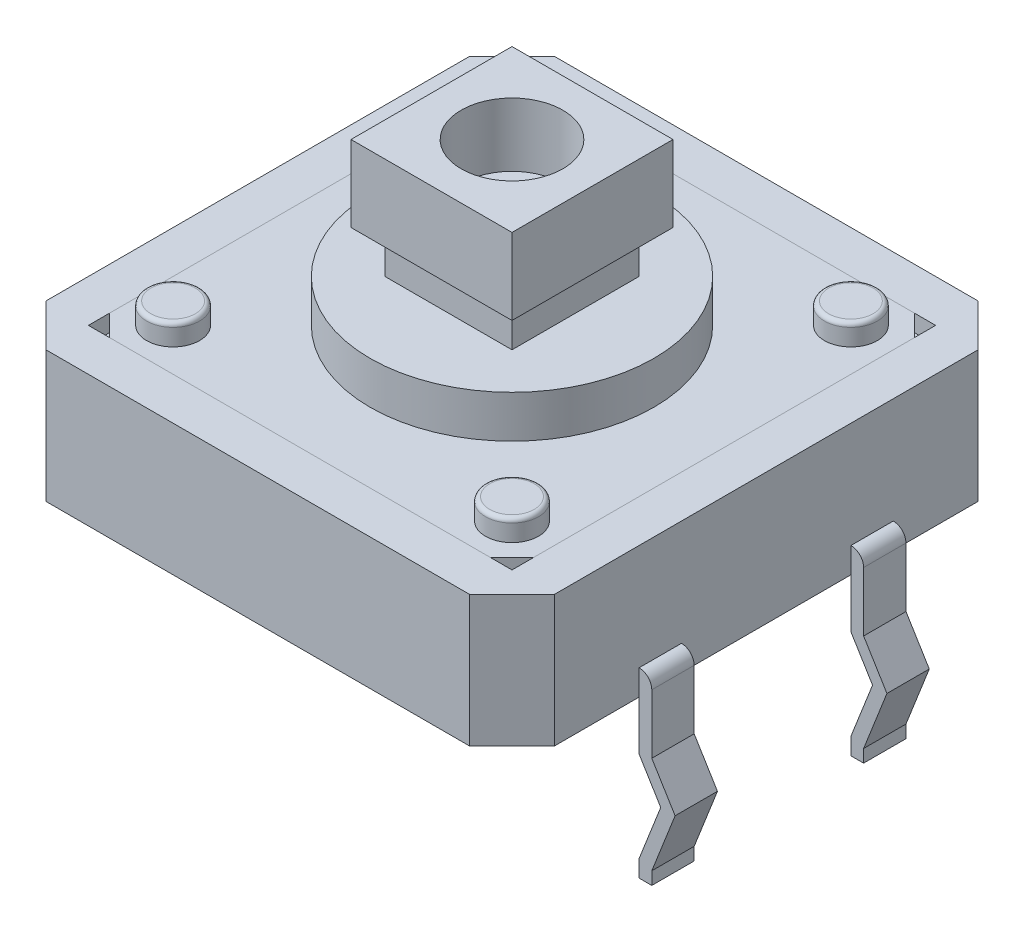
SolidWorks part; units mm, degrees
other "Markup1"
sketch "Sketch10" plane through (-6.85, 6.9, 6) normal (-0.3058, 0.046, 0.951) x (0.9335, 0.2107, 0.29)
sketch "Sketch13" plane through (-6.85, 6.9, 6) normal (-0.3058, 0.046, 0.951) x (0.9335, 0.2107, 0.29)
ref_plane "Front Plane" through (0, 0, 0) normal (0, 0, 1) x (1, 0, 0)
ref_plane "Top Plane" through (0, 0, 0) normal (0, 1, 0) x (1, 0, 0)
ref_plane "Right Plane" through (0, 0, 0) normal (1, 0, 0) x (0, 0, -1)
sketch "Sketch1" plane through (0, 0, 0) normal (0, 1, 0) x (1, 0, 0)
  line L0 (-5, 6) -> (-6, 5)
  line L1 (5, -6) -> (-5, -6)
  line L2 (6, -5) -> (6, 5)
  line L3 (5, 6) -> (-5, 6)
  line L4 (-6, -5) -> (-6, 5)
  line L5 (6, -6) -> (-6, 6) construction
  line L6 (6, 6) -> (-6, -6) construction
  line L7 (-5, -6) -> (-6, -5)
  line L8 (6, -5) -> (5, -6)
  line L9 (6, 5) -> (5, 6)
  point P0 (0, 0)
  dimension "D1" = 12
extrude "Boss-Extrude1" add sketch "Sketch1" along normal blind 3.1
sketch "Sketch2" plane through (0, 3.1, 0) normal (0, 1, 0) x (1, 0, 0)
  line L1 (5, -5) -> (-5, -5)
  line L2 (5, -5) -> (5, 5)
  line L3 (5, 5) -> (-5, 5)
  line L4 (-5, -5) -> (-5, 5)
  line L5 (5, -5) -> (-5, 5) construction
  line L6 (5, 5) -> (-5, -5) construction
  point P0 (0, 0)
  dimension "D1" = 10
extrude "Cut-Extrude1" cut sketch "Sketch2" against normal blind 0.4
sketch "Sketch3" plane through (0, 2.7, 0) normal (0, 1, 0) x (1, 0, 0)
  line L1 (4, -4) -> (-4, -4) construction
  line L2 (4, -4) -> (4, 4) construction
  line L3 (4, 4) -> (-4, 4) construction
  line L4 (-4, -4) -> (-4, 4) construction
  line L5 (4, -4) -> (-4, 4) construction
  line L6 (4, 4) -> (-4, -4) construction
  circle A0 centre (-4, 4) radius 0.625
  circle A1 centre (4, 4) radius 0.625
  circle A2 centre (-4, -4) radius 0.625
  circle A3 centre (4, -4) radius 0.625
  point P0 (0, 0)
  dimension "D2" = 1.25
  dimension "D1" = 8
extrude "Boss-Extrude2" add sketch "Sketch3" along normal blind 0.9
fillet "Fillet1" radius 0.1 4 edges at (4, 3.6, -3.375) (4, 3.6, 4.625) (-4, 3.6, 4.625) (-4, 3.6, -3.375)
sketch "Sketch4" plane through (0, 2.7, 0) normal (0, 1, 0) x (1, 0, 0)
  line L0 (5, 5) -> (-5, 5) construction
  line L1 (4.5, -5) -> (-4.5, -5)
  line L2 (5, -4.5) -> (5, 4.5)
  line L3 (4.5, 5) -> (-4.5, 5)
  line L4 (-5, -4.5) -> (-5, 4.5)
  line L5 (5, -5) -> (-5, 5) construction
  line L6 (5, 5) -> (-5, -5) construction
  line L9 (-5, 5) -> (-5, -5) construction
  line L10 (-4.5, 5) -> (-5, 4.5)
  line L11 (5, 4.5) -> (4.5, 5)
  line L12 (-4.5, -5) -> (-5, -4.5)
  line L13 (5, -4.5) -> (4.5, -5)
  circle A0 centre (0, 0) radius 3.35
  point P0 (0, 0)
  dimension "D2" = 6.7
extrude "Boss-Extrude3" add sketch "Sketch4" along normal blind 0.4 separate body
sketch "Sketch5" plane through (0, 0, 0) normal (0, 0, 1) x (1, 0, 0)
  line L1 (6, 3.1) -> (6, 0) construction
  line L2 (6, 0.6) -> (6, -1.1643)
  line L3 (6, -3.7) -> (6.3, -3.7)
  line L4 (6.3, -3.7) -> (6.3, -3.4)
  line L5 (6.3, -3.4) -> (6.85, -2)
  line L6 (6.85, -2) -> (6.3, -1.1)
  line L7 (6.3, -1.1) -> (6.3, 0.3)
  line L10 (6, -3.3) -> (6, -3.7)
  line L11 (6, 0.6) -> (6.3033, 0.6) construction
  line L12 (6.5107, -2) -> (6, -1.1643)
  line L13 (6, 0.3) -> (6.3, 0.3) construction
  line L14 (6.5107, -2) -> (6, -3.3)
  arc A0 (6, 0.6) -> (6.3, 0.3) centre (6, 0.3) cw
  point P15 (6.15, -3.7)
  dimension "D1" = 2.5
  dimension "D2" = 6.85
  dimension "D3" = 0.3
  dimension "D4" = 6.15
  dimension "D5" = 2
  dimension "D6" = 3.7
  dimension "D7" = 0.9
  dimension "D8" = 1.4
  dimension "D9" = 0.1
extrude "Boss-Extrude4" add sketch "Sketch5" along normal blind 3 and the other way blind 3 separate body
sketch "Sketch6" plane through (0, 0, 0) normal (0, 1, 0) x (1, 0, 0)
  line L5 (6, 2) -> (6.85, 2)
  line L6 (6, 2) -> (6, -2)
  line L7 (6, -2) -> (6.85, -2)
  line L8 (6.85, 2) -> (6.85, -2)
  line L9 (6, -5) -> (6, 5) construction
  line L11 (6.85, 3) -> (6.85, -3) construction
  point P8 (6, 0)
  dimension "D1" = 4
extrude "Cut-Extrude2" cut sketch "Sketch6" against normal through all both and the other way through all
sketch "Sketch7" plane through (0, 2.7, 0) normal (0, 1, 0) x (1, 0, 0)
  circle A0 centre (0, 0) radius 3.35 construction
  circle A1 centre (0, 0) radius 3.35
extrude "Boss-Extrude5" add sketch "Sketch7" along normal blind 1.4 separate body
sketch "Sketch8" plane through (0, 4.1, 0) normal (0, 1, 0) x (1, 0, 0)
  line L1 (1.5, -1.5) -> (-1.5, -1.5)
  line L2 (1.5, -1.5) -> (1.5, 1.5)
  line L3 (1.5, 1.5) -> (-1.5, 1.5)
  line L4 (-1.5, -1.5) -> (-1.5, 1.5)
  line L5 (1.5, -1.5) -> (-1.5, 1.5) construction
  line L6 (1.5, 1.5) -> (-1.5, -1.5) construction
  point P0 (0, 0)
  dimension "D1" = 3
extrude "Boss-Extrude6" add sketch "Sketch8" along normal blind 1
sketch "Sketch9" plane through (0, 5.1, 0) normal (0, 1, 0) x (1, 0, 0)
  line L1 (1.9, -1.9) -> (-1.9, -1.9)
  line L2 (1.9, -1.9) -> (1.9, 1.9)
  line L3 (1.9, 1.9) -> (-1.9, 1.9)
  line L4 (-1.9, -1.9) -> (-1.9, 1.9)
  line L5 (1.9, -1.9) -> (-1.9, 1.9) construction
  line L6 (1.9, 1.9) -> (-1.9, -1.9) construction
  point P0 (0, 0)
  dimension "D1" = 3.8
extrude "Boss-Extrude7" add sketch "Sketch9" along normal blind 1.8
sketch "Sketch11" plane through (0, 6.9, 0) normal (0, 1, 0) x (1, 0, 0)
  circle A0 centre (0, 0) radius 1.2
  dimension "D1" = 2.4
extrude "Cut-Extrude3" cut sketch "Sketch11" against normal blind 1.5
sketch "Sketch12" plane through (0, 0, 0) normal (0, -1, 0) x (1, 0, 0)
  line L6 (3, 5.5) -> (3, 3.7)
  line L7 (3, 3.7) -> (5.5, 3.7)
  line L8 (5.83, 0) -> (-5.83, 0) construction
  line L9 (5.5, 4.7929) -> (5.5, -5)
  line L10 (-5, 5.5) -> (4.7929, 5.5)
  line L11 (4.7929, 5.5) -> (5.5, 4.7929)
  line L12 (5.5, 4.7929) -> (5.5, 3.7)
  line L13 (3, 5.5) -> (4.7929, 5.5)
  line L14 (4.7929, 5.5) -> (5.5, 4.7929)
  line L15 (4.7929, -5.5) -> (5.5, -4.7929)
  line L16 (3, -5.5) -> (4.7929, -5.5)
  line L17 (5.5, -4.7929) -> (5.5, -3.7)
  line L18 (3, -3.7) -> (5.5, -3.7)
  line L19 (3, -5.5) -> (3, -3.7)
  line L20 (0, -5.83) -> (0, 5.83) construction
  line L21 (-3, -5.5) -> (-3, -3.7)
  line L22 (-3, -3.7) -> (-5.5, -3.7)
  line L23 (-5.5, -4.7929) -> (-5.5, -3.7)
  line L24 (-3, -5.5) -> (-4.7929, -5.5)
  line L25 (-4.7929, -5.5) -> (-5.5, -4.7929)
  line L26 (-4.7929, 5.5) -> (-5.5, 4.7929)
  line L27 (-3, 5.5) -> (-4.7929, 5.5)
  line L28 (-5.5, 4.7929) -> (-5.5, 3.7)
  line L29 (-3, 3.7) -> (-5.5, 3.7)
  line L30 (-3, 5.5) -> (-3, 3.7)
  dimension "D2" = 2.5
  dimension "D3" = 1.8
  dimension "D1" = 0.5
extrude "Boss-Extrude8" add sketch "Sketch12" along normal blind 0.2
